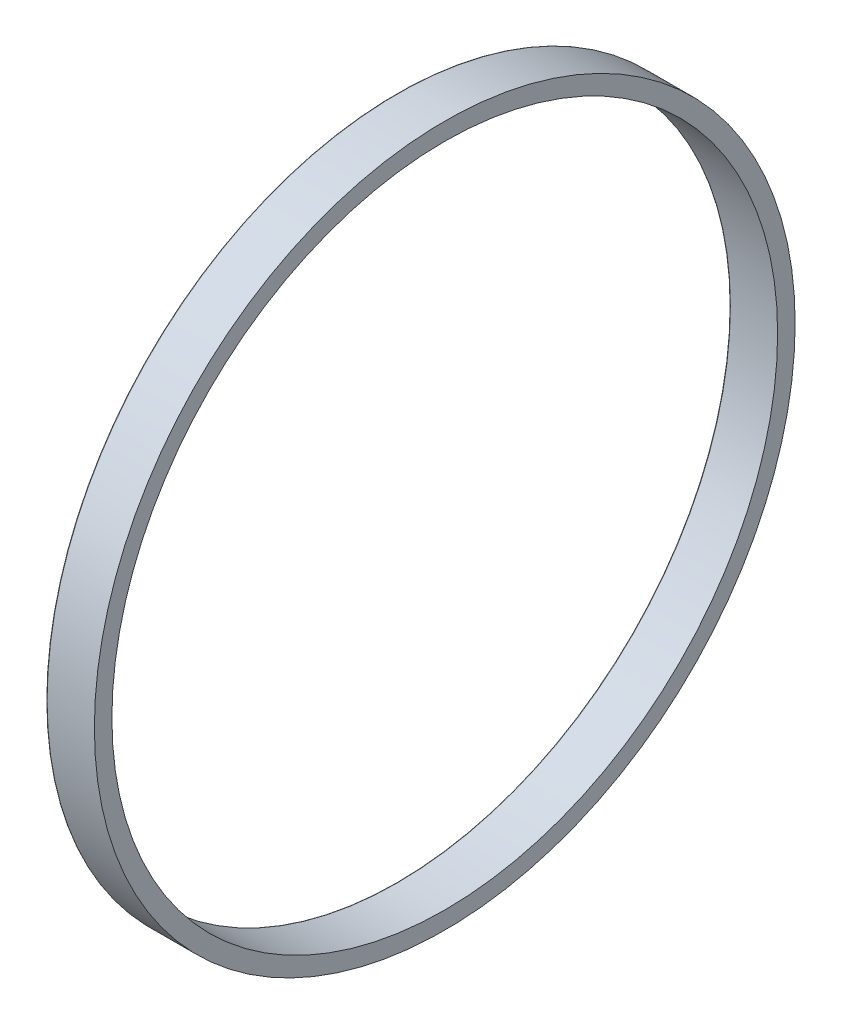
SolidWorks part; units mm, degrees
material "PP Copolymer"
ref_plane "Ön Düzlem" through (0, 0, 0) normal (0, 0, 1) x (1, 0, 0)
ref_plane "Üst Düzlem" through (0, 0, 0) normal (0, 1, 0) x (1, 0, 0)
ref_plane "Sağ Düzlem" through (0, 0, 0) normal (1, 0, 0) x (0, 0, -1)
sketch "Sketch1" plane through (0, 0, 0) normal (0, 0, 1) x (1, 0, 0)
  line L0 (-83.2087, 0) -> (78.4468, 0) construction
  line L1 (-37.8095, -40) -> (-32.4257, -40)
  line L2 (-37.8095, -38) -> (-32.4257, -38)
  line L3 (-32.4257, -38) -> (-32.4257, -40)
  line L4 (-37.8411, -38.1949) -> (-35.995, -38.8103)
  line L5 (-35.995, -39.1897) -> (-37.8411, -39.8051)
  arc A0 (-35.995, -38.8103) -> (-35.995, -39.1897) centre (-36.0582, -39) cw
  arc A1 (-37.8095, -38) -> (-37.8411, -38.1949) centre (-37.8095, -38.1) ccw
  arc A2 (-37.8095, -40) -> (-37.8411, -39.8051) centre (-37.8095, -39.9) cw
  point P14 (-38.4257, -40)
  dimension "D4" = 0.2
  dimension "D5" = 0.1
  dimension "D1" = 40
  dimension "D2" = 6
  dimension "D3" = 38
revolve "Revolve1" add sketch "Sketch1" angle 360 about L0
